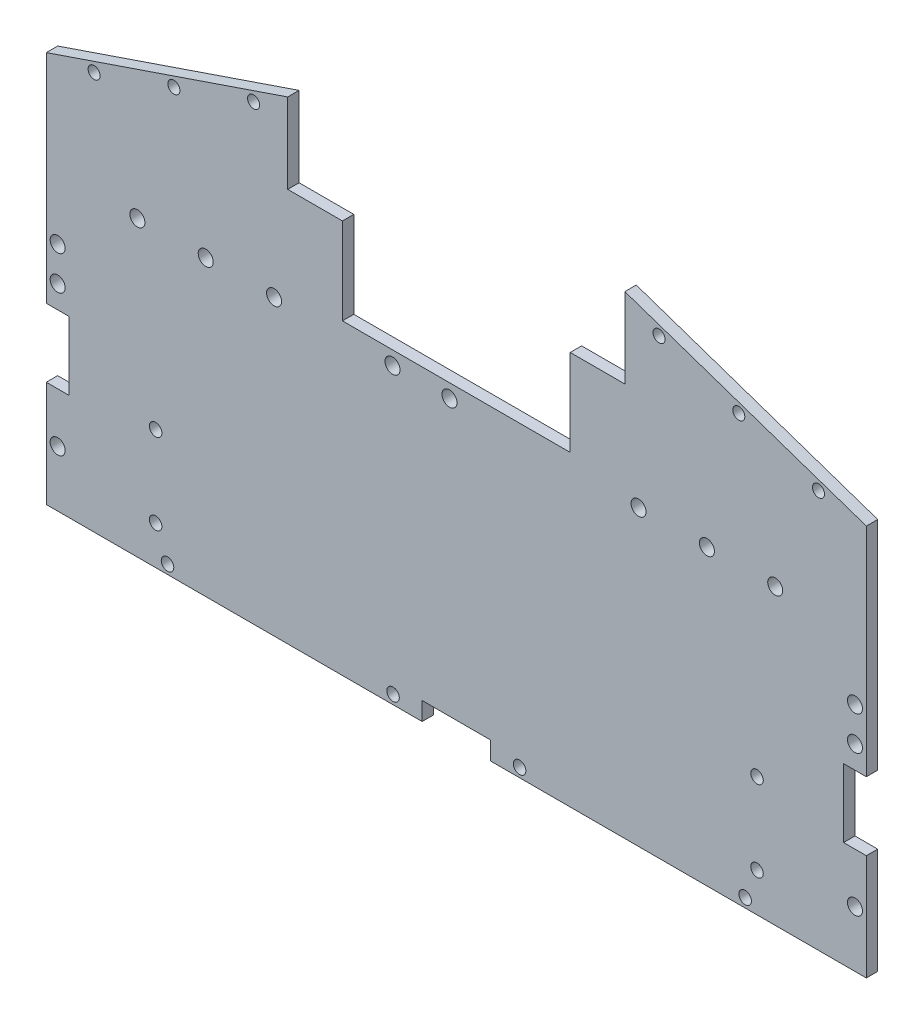
SolidWorks part; units mm, degrees
material "7075-T6, Chapa (SS)"
ref_plane "Plano frontal" through (0, 0, 0) normal (0, 0, 1) x (1, 0, 0)
ref_plane "Plano superior" through (0, 0, 0) normal (0, 1, 0) x (1, 0, 0)
ref_plane "Plano direito" through (0, 0, 0) normal (1, 0, 0) x (0, 0, -1)
sketch "Esboço1" plane through (0, 0, 0) normal (0, 0, 1) x (1, 0, 0)
  line L0 (230, 172.82) -> (360, 172.82)
  line L1 (0, 0) -> (360, 0)
  line L2 (0, 0) -> (0, 172.82)
  line L3 (0, 172.82) -> (130, 172.82)
  line L4 (360, 0) -> (360, 172.82)
  line L6 (130, 172.82) -> (130, 134.82)
  line L8 (230, 172.82) -> (230, 134.82)
  line L9 (130, 134.82) -> (230, 134.82)
  dimension "D1" = 360
  dimension "D2" = 172.82
  dimension "D3" = 38
  dimension "D4" = 100
extrude "Ressalto-extrusão1" add sketch "Esboço1" along normal blind 5
sketch "Esboço2" plane through (0, 0, 5) normal (0, 0, 1) x (1, 0, 0)
  line L0 (0, 172.82) -> (0, 0) construction
  line L5 (180, 134.82) -> (180, 0) construction
  line L7 (0, 0) -> (360, 0) construction
  line L8 (230, 134.82) -> (130, 134.82) construction
  line L14 (0, 46.5) -> (10, 46.5)
  line L15 (0, 46.5) -> (0, 76.5)
  line L16 (0, 76.5) -> (10, 76.5)
  line L17 (10, 46.5) -> (10, 76.5)
  line L18 (360, 76.5) -> (350, 76.5)
  line L19 (350, 46.5) -> (350, 76.5)
  line L20 (360, 46.5) -> (350, 46.5)
  line L21 (360, 46.5) -> (360, 76.5)
  line L31 (165, 0) -> (195, 0)
  line L32 (165, 0) -> (165, 8)
  line L33 (165, 8) -> (195, 8)
  line L34 (195, 0) -> (195, 8)
  dimension "D2" = 10
  dimension "D3" = 30
  dimension "D6" = 46.5
  dimension "D10" = 30
  dimension "D11" = 8
extrude "Corte-extrusão1" cut sketch "Esboço2" against normal blind 5
sketch "Esboço3" plane through (0, 0, 5) normal (0, 0, 1) x (1, 0, 0)
  line L0 (360, 172.82) -> (360, 187.82)
  line L3 (0, 187.82) -> (110, 227.82)
  line L5 (360, 172.82) -> (230, 172.82) construction
  line L7 (250, 172.82) -> (250, 227.82)
  line L8 (250, 227.82) -> (360, 187.82)
  line L10 (250, 172.82) -> (360, 172.82)
  line L11 (0, 172.82) -> (0, 187.82)
  line L13 (0, 172.82) -> (110, 172.82)
  line L14 (130, 172.82) -> (0, 172.82) construction
  line L16 (110, 172.82) -> (110, 227.82)
  dimension "D1" = 55
  dimension "D2" = 15
  dimension "D3" = 55
  dimension "D4" = 110
  dimension "D6" = 110
  dimension "D7" = 15
extrude "Ressalto-extrusão2" add sketch "Esboço3" against normal up to surface (5 mm away) up to face at (180, 73.446, 0)
hole_wizard "Furo com folga de M61" positions "Esboço4" profile "Esboço5" hole size "M6" standard "ISO" end condition through all
sketch "Esboço4" plane through (0, 0, 0) normal (0, 0, -1) x (-1, 0, 0)
  line L1 (-360, 76.5) -> (-360, 187.82) construction
  line L2 (-195, 0) -> (-360, 0) construction
  line L3 (-360, 76.5) -> (-350, 76.5) construction
  line L5 (-10, 76.5) -> (0, 76.5) construction
  line L7 (0, 187.82) -> (0, 76.5) construction
  line L8 (-320, 128.82) -> (-40, 128.82) construction
  line L9 (-350, 46.5) -> (-360, 46.5) construction
  line L10 (0, 46.5) -> (-10, 46.5) construction
  line L12 (-355, 0) -> (-355, 189.6382) construction
  line L13 (-360, 187.82) -> (-250, 227.82) construction
  line L14 (-5, 0) -> (-5, 189.6382) construction
  line L15 (0, 0) -> (-165, 0) construction
  line L16 (-110, 227.82) -> (0, 187.82) construction
  line L17 (-230, 172.82) -> (-230, 134.82) construction
  line L18 (-130, 134.82) -> (-130, 172.82) construction
  point P2 (-355, 24.65)
  point P4 (-355, 86.5)
  point P10 (-5, 24.65)
  point P12 (-5, 86.5)
  point P34 (-320, 128.82)
  point P36 (-290, 128.82)
  point P38 (-70, 128.82)
  point P40 (-40, 128.82)
  point P50 (-177, 128.82)
  point P77 (-355, 101.5)
  point P88 (-5, 101.5)
  point P110 (-260, 128.82)
  point P112 (-100, 128.82)
  point P114 (-152, 128.82)
  dimension "D3" = 5
  dimension "D4" = 21.85
  dimension "D5" = 21.85
  dimension "D7" = 10
  dimension "D11" = 10
  dimension "D12" = 5
  dimension "D13" = 15
  dimension "D17" = 128.82
  dimension "D18" = 30
  dimension "D19" = 30
  dimension "D20" = 30
  dimension "D21" = 30
  dimension "D23" = 15
  dimension "D24" = 30
  dimension "D25" = 30
  dimension "D26" = 22
  dimension "D27" = 25
sketch "Esboço5" plane through (355, 24.65, 0) normal (1, 0, 0) x (0, 1, 0)
  line L0 (0, 0) -> (0, 5)
  line L1 (0, 5) -> (3.3, 5)
  line L2 (3.3, 5) -> (3.3, 0)
  line L5 (3.3, 0) -> (0, 0)
  line L11 (0, -6.35) -> (0, 107.95) construction
  dimension "Thru Hole Dia." = 6.6
  dimension "Thru Hole Depth" = 5
hole_wizard "Furo com folga de M51" positions "Esboço6" profile "Esboço7" hole size "M5" standard "ISO" end condition through all
sketch "Esboço6" plane through (0, 0, 0) normal (0, 0, -1) x (-1, 0, 0)
  line L0 (-195, 0) -> (-360, 0) construction
  line L1 (-360, 0) -> (-360, 46.5) construction
  line L6 (-312, 17) -> (-312, 52.5) construction
  line L8 (-360, 4) -> (0, 4) construction
  line L9 (0, 46.5) -> (0, 0) construction
  point P0 (-312, 17)
  point P37 (-312, 52.5)
  point P46 (-306.78, 4)
  point P48 (-207.78, 4)
  point P50 (-152.22, 4)
  point P52 (-53.22, 4)
  dimension "D1" = 17
  dimension "D2" = 48
  dimension "D3" = 35.5
  dimension "D4" = 4
  dimension "D7" = 53.22
  dimension "D8" = 99
  dimension "D9" = 53.22
  dimension "D10" = 99
sketch "Esboço7" plane through (312, 17, 0) normal (1, 0, 0) x (0, 1, 0)
  line L0 (0, 0) -> (0, 5)
  line L1 (0, 5) -> (2.75, 5)
  line L2 (2.75, 5) -> (2.75, 0)
  line L5 (2.75, 0) -> (0, 0)
  line L11 (0, -6.35) -> (0, 107.95) construction
  dimension "Thru Hole Dia." = 5.5
  dimension "Thru Hole Depth" = 5
ref_plane "Plano1" through (180, 0, 0) normal (1, 0, 0) x (0, 0, -1)
mirror "Espelhar1" about plane through (180, 0, 0) normal (1, 0, 0) of "Furo com folga de M51"
sketch "Esboço8" plane through (0, 0, 5) normal (0, 0, 1) x (1, 0, 0)
  line L0 (0, 187.82) -> (110, 227.82)
  line L1 (110, 227.82) -> (110, 209.32)
  line L2 (110, 172.82) -> (110, 227.82) construction
  line L3 (110, 209.32) -> (0, 171.82)
  line L4 (0, 187.82) -> (0, 76.5) construction
  line L5 (0, 171.82) -> (0, 187.82)
  line L6 (180, -2.75) -> (180, 2.75) construction
  line L7 (250, 209.32) -> (360, 171.82)
  line L8 (250, 227.82) -> (250, 209.32)
  line L9 (360, 187.82) -> (250, 227.82)
  line L10 (360, 171.82) -> (360, 187.82)
  dimension "D1" = 16
  dimension "D2" = 18.5
extrude "Corte-extrusão2" cut sketch "Esboço8" against normal through all
sketch "Esboço9" plane through (0, 0, 5) normal (0, 0, 1) x (1, 0, 0)
  line L0 (110, 172.82) -> (106, 172.82)
  line L1 (106, 172.82) -> (106, 272.82)
  line L2 (106, 272.82) -> (110, 272.82)
  line L3 (110, 272.82) -> (110, 172.82)
  line L4 (250, 172.82) -> (254, 172.82)
  line L5 (254, 172.82) -> (254, 272.82)
  line L6 (254, 272.82) -> (250, 272.82)
  line L7 (250, 272.82) -> (250, 172.82)
  dimension "D1" = 4
  dimension "D2" = 4
  dimension "D3" = 100
  dimension "D4" = 100
extrude "Corte-extrusão3" cut sketch "Esboço9" against normal through all
hole_wizard "Furo com folga de M52" positions "Esboço10" profile "Esboço11" hole size "M5" standard "ISO"
sketch "Esboço10" plane through (0, 0, 5) normal (0, 0, 1) x (1, 0, 0)
  line L0 (91, 198.6167) -> (21, 174.753) construction
  line L2 (0, 171.82) -> (106, 207.9564) construction
  line L3 (106, 207.9564) -> (106, 172.82) construction
  point P0 (91, 198.6167)
  point P2 (56, 186.6849)
  point P4 (21, 174.753)
  dimension "D1" = 4
  dimension "D2" = 15
  dimension "D3" = 35
  dimension "D4" = 70
sketch "Esboço11" plane through (91, 198.6167, 5) normal (1, 0, 0) x (0, -1, 0)
  line L0 (0, 0) -> (0, 16.5923)
  line L1 (0, 16.5923) -> (2.65, 15)
  line L2 (2.65, 15) -> (2.65, 0)
  line L5 (2.65, 0) -> (0, 0)
  line L10 (0, 16.5923) -> (-2.65, 15) construction
  line L11 (0, -6.35) -> (0, 107.95) construction
  dimension "Hole Dia." = 5.3
  dimension "Hole Depth" = 15
  dimension "Drill Angle" = 118
mirror "Espelhar2" about plane through (180, 0, 0) normal (1, 0, 0) of "Furo com folga de M52"
